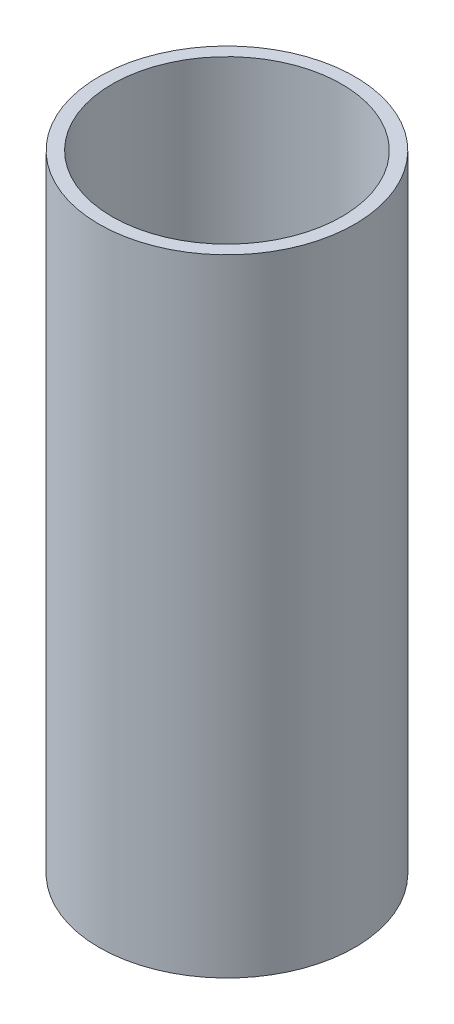
SolidWorks part; units mm, degrees
ref_plane "Front Plane" through (0, 0, 0) normal (0, 0, 1) x (1, 0, 0)
ref_plane "Top Plane" through (0, 0, 0) normal (0, 1, 0) x (1, 0, 0)
ref_plane "Right Plane" through (0, 0, 0) normal (1, 0, 0) x (0, 0, -1)
sketch "Sketch1" plane through (0, 0, 0) normal (0, 1, 0) x (1, 0, 0)
  circle A0 centre (0, 0) radius 4.9
  circle A1 centre (0, 0) radius 4.4
  dimension "D1" = 9.8
  dimension "D2" = 8.8
extrude "Boss-Extrude1" add sketch "Sketch1" along normal mid plane 24
